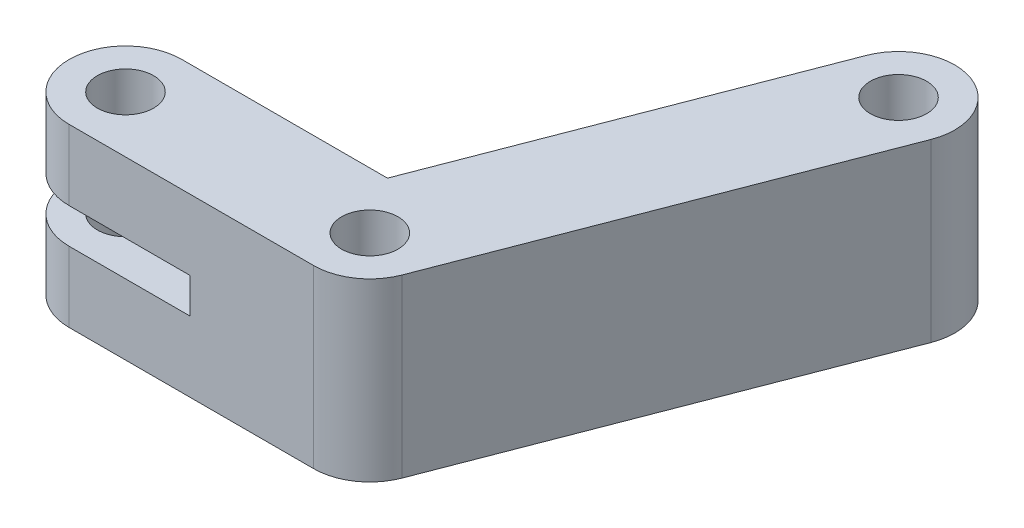
SolidWorks part; units mm, degrees
ref_plane "前视基准面" through (0, 0, 0) normal (0, 0, 1) x (1, 0, 0)
ref_plane "上视基准面" through (0, 0, 0) normal (0, 1, 0) x (1, 0, 0)
ref_plane "右视基准面" through (0, 0, 0) normal (1, 0, 0) x (0, 0, -1)
sketch "草图1" plane through (0, 0, 0) normal (0, 1, 0) x (1, 0, 0)
  line L0 (0, 8) -> (29.2283, 8)
  line L1 (29.2283, 8) -> (48.1445, 57.1152)
  line L2 (63.0755, 51.3648) -> (42.1855, -2.8752)
  line L3 (34.72, -8) -> (0, -8)
  line L4 (55.61, 54.24) -> (34.72, 0) construction
  circle A0 centre (0, 0) radius 4
  arc A1 (0, -8) -> (0, 8) centre (0, 0) cw
  arc A2 (48.1445, 57.1152) -> (63.0755, 51.3648) centre (55.61, 54.24) cw
  circle A3 centre (34.72, 0) radius 4
  circle A4 centre (55.61, 54.24) radius 4
  arc A5 (42.1855, -2.8752) -> (34.72, -8) centre (34.72, 0) cw
  dimension "D1" = 8
  dimension "D2" = 8
  dimension "D3" = 8
  dimension "D4" = 8
  dimension "D5" = 8
  dimension "D9" = 8
  dimension "D6" = 34.72
  dimension "D7" = 54.24
  dimension "D8" = 20.89
extrude "凸台-拉伸1" add sketch "草图1" along normal mid plane 25
sketch "草图2" plane through (0, 0, 8) normal (0, 0, 1) x (1, 0, 0)
  line L0 (-8, 12.5) -> (-8, -12.5) construction
  line L1 (-8, 2.5) -> (17.15, 2.5)
  line L2 (-8, 2.5) -> (-8, -2.5)
  line L3 (-8, -2.5) -> (17.15, -2.5)
  line L4 (17.15, 2.5) -> (17.15, -2.5)
  point P4 (-8, 0)
  dimension "D1" = 25.15
  dimension "D2" = 5
extrude "切除-拉伸1" cut sketch "草图2" along direction (0, 0, 1) on the side against the normal up to next (16 mm away)
